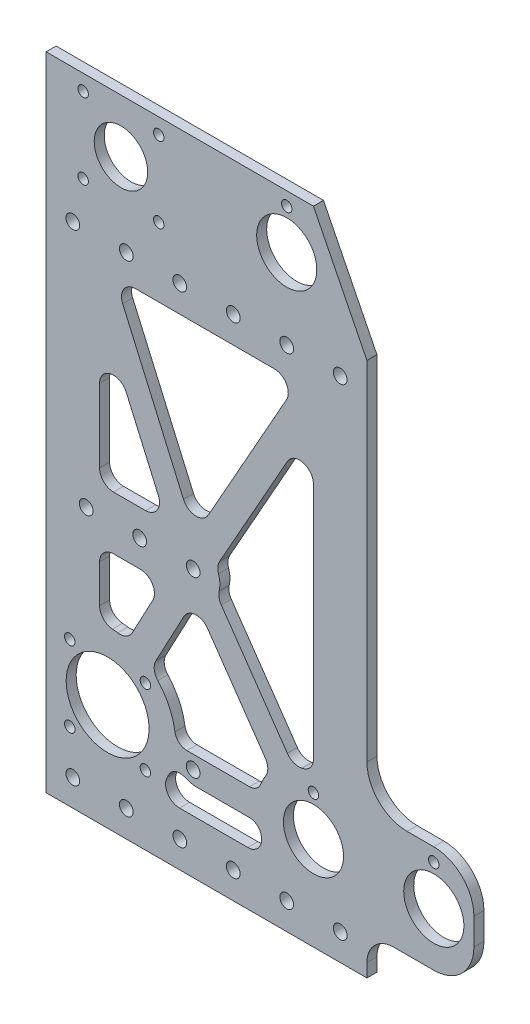
SolidWorks part; units mm, degrees
material "6061 Alloy"
ref_plane "Front Plane" through (0, 0, 0) normal (0, 0, 1) x (1, 0, 0)
ref_plane "Top Plane" through (0, 0, 0) normal (0, 1, 0) x (1, 0, 0)
ref_plane "Right Plane" through (0, 0, 0) normal (1, 0, 0) x (0, 0, -1)
sketch "Sketch1" plane through (0, 0, 0) normal (0, 0, 1) x (1, 0, 0)
  line L0 (0, 0) -> (76.2, 0) construction
  line L1 (76.2, 0) -> (76.2, 25.4)
  line L2 (76.2, 25.4) -> (50.8, 76.2)
  line L3 (50.8, 76.2) -> (12.7, 76.2)
  line L6 (-63.5, 12.7) -> (-38.1, 12.7) construction
  line L7 (76.2, 0) -> (76.2, -139.7)
  line L8 (0, 0) -> (-76.2, 0) construction
  line L9 (-76.2, 0) -> (-76.2, 76.2)
  line L10 (-76.2, 76.2) -> (12.7, 76.2)
  line L11 (76.2, -228.6) -> (0, -228.6)
  line L13 (63.5, -215.9) -> (38.1, -215.9) construction
  line L14 (-57.15, -101.6) -> (-31.75, -101.6) construction
  line L18 (95.25, -158.75) -> (107.95, -158.75)
  line L19 (127, -177.8) -> (127, -190.5)
  line L20 (107.95, -209.55) -> (88.9, -209.55)
  line L22 (76.2, -222.25) -> (76.2, -228.6)
  line L24 (-76.2, -177.8) -> (-46.99, -177.8) construction
  line L25 (-46.99, -177.8) -> (-29.0295, -195.7605) construction
  line L26 (-46.99, -177.8) -> (-29.0295, -195.7605) construction
  line L27 (-46.99, -177.8) -> (-64.9505, -195.7605) construction
  line L28 (-76.2, -228.6) -> (-76.2, 0)
  line L29 (0, -228.6) -> (-76.2, -228.6)
  circle A2 centre (-38.1, 12.7) radius 3.2639
  circle A3 centre (-12.7, 12.7) radius 3.2639
  circle A6 centre (-63.5, 12.7) radius 3.2639
  circle A7 centre (12.7, 12.7) radius 3.2639
  circle A8 centre (38.1, 12.7) radius 3.2639
  circle A9 centre (38.1, 50.8) radius 14.2875
  circle A12 centre (-22.6795, 32.8395) radius 2.4892
  circle A13 centre (-58.6005, 32.8395) radius 2.4892
  circle A14 centre (-58.6005, 68.7605) radius 2.4892
  circle A15 centre (-22.6795, 68.7605) radius 2.4892
  circle A16 centre (63.5, 12.7) radius 3.2639
  circle A17 centre (-40.64, 50.8) radius 12.7
  circle A18 centre (50.8, -184.15) radius 14.2875
  circle A19 centre (63.5, -215.9) radius 3.2639
  circle A20 centre (38.1, -215.9) radius 3.2639
  circle A21 centre (12.7, -215.9) radius 3.2639
  circle A22 centre (50.8, -165.1) radius 2.4892
  circle A23 centre (38.1, 69.85) radius 2.4892
  circle A26 centre (-6.35, -184.15) radius 3.2639
  circle A27 centre (107.95, -184.15) radius 14.2875
  circle A28 centre (107.95, -165.1) radius 2.4892
  circle A29 centre (-57.15, -101.6) radius 3.2639
  circle A30 centre (-31.75, -101.6) radius 3.2639
  circle A31 centre (-6.35, -101.6) radius 3.2639
  arc A32 (127, -190.5) -> (107.95, -209.55) centre (107.95, -190.5) cw
  arc A33 (76.2, -139.7) -> (95.25, -158.75) centre (95.25, -139.7) ccw
  arc A34 (127, -177.8) -> (107.95, -158.75) centre (107.95, -177.8) ccw
  arc A35 (76.2, -222.25) -> (88.9, -209.55) centre (88.9, -222.25) cw
  circle A36 centre (-46.99, -177.8) radius 19.685
  circle A37 centre (-46.99, -177.8) radius 25.4 construction
  circle A38 centre (-29.0295, -195.7605) radius 2.4892
  circle A42 centre (-64.9505, -195.7605) radius 2.4892
  circle A43 centre (-64.9505, -159.8395) radius 2.4892
  circle A44 centre (-29.0295, -159.8395) radius 2.4892
  circle A45 centre (-12.7, -215.9) radius 3.2639
  circle A46 centre (-38.1, -215.9) radius 3.2639
  circle A47 centre (-63.5, -215.9) radius 3.2639
  point P40 (-40.64, 50.8)
  point P71 (127, -209.55)
  point P74 (76.2, -158.75)
  point P77 (127, -158.75)
  point P80 (76.2, -209.55)
  dimension "D7" = 12.7
  dimension "D14" = 6.5278
  dimension "D16" = 28.575
  dimension "D18" = 50.8
  dimension "D20" = 12.7
  dimension "D21" = 4.9784
  dimension "D10" = 25.4
  dimension "D13" = 228.6
  dimension "D28" = 4.9784
  dimension "D29" = 4.9784
  dimension "D34" = 19.05
  dimension "D35" = 19.05
  dimension "D39" = 6.5278
  dimension "D41" = 6.5278
  dimension "D46" = 19.05
  dimension "D47" = 12.7
  dimension "D48" = 39.37
  dimension "D49" = 50.8
  dimension "D52" = 45
  dimension "D55" = 4.9784
  dimension "D1" = 76.2
  dimension "D2" = 76.2
  dimension "D3" = 88.9
  dimension "D4" = 38.1
  dimension "D5" = 25.4
  dimension "D6" = 38.1
  dimension "D8" = 6
  dimension "D11" = 25.4
  dimension "D12" = 184.15
  dimension "D15" = 35.56
  dimension "D17" = 50.8
  dimension "D19" = 25.4
  dimension "D23" = 12.7
  dimension "D9" = 25.4
  dimension "D25" = 25.4
  dimension "D26" = 76.2
  dimension "D27" = 19.05
  dimension "D30" = 19.05
  dimension "D31" = 50.8
  dimension "D32" = 19.05
  dimension "D33" = 76.2
  dimension "D36" = 25.4
  dimension "D37" = 50.8
  dimension "D38" = 6.35
  dimension "D40" = 76.2
  dimension "D42" = 127
  dimension "D43" = 57.15
  dimension "D45" = 25.4
  dimension "D53" = 46.99
  dimension "D54" = 50.8
  dimension "D58" = 90
  dimension "D24" = 6
  dimension "D44" = 3
  dimension "D22" = 4
  dimension "D57" = 4
extrude "Boss-Extrude1" add sketch "Sketch1" along normal blind 4.7625
sketch "Sketch2" plane through (0, 0, 4.7625) normal (0, 0, 1) x (1, 0, 0)
  line L3 (19.5993, -203.2) -> (-12.8308, -203.2)
  line L6 (-76.2, 76.2) -> (-76.2, -228.6) construction
  line L7 (50.8, 0) -> (-6.35, -101.6) construction
  line L8 (50.8, -157.1625) -> (50.8, -203.2) construction
  line L9 (-76.2, -228.6) -> (76.2, -228.6) construction
  line L10 (-46.99, -177.8) -> (-6.35, -101.6) construction
  line L11 (32.2225, 0) -> (-33.7713, 0)
  line L12 (50.8, 76.2) -> (-76.2, 76.2) construction
  line L13 (76.2, -228.6) -> (-76.2, -228.6)
  line L14 (-76.2, -228.6) -> (-76.2, 25.4)
  line L15 (-76.2, 25.4) -> (76.2, 25.4)
  line L16 (76.2, 25.4) -> (76.2, -228.6)
  line L17 (-6.35, -101.6) -> (-57.15, -101.6) construction
  line L20 (50.8, -184.15) -> (-6.35, -101.6) construction
  line L21 (7.0176, -109.7529) -> (38.3792, -155.0531)
  line L22 (27.9374, -162.2821) -> (0.5166, -122.6742)
  line L23 (-35.2875, -142.364) -> (-25.4996, -124.0118)
  line L24 (-10.7403, -123.3255) -> (-24.0816, -148.3405)
  line L25 (6.2012, -92.239) -> (38.4401, -34.9254)
  line L26 (-31.3267, -114.3) -> (-44.196, -114.3)
  line L27 (-6.35, -101.6) -> (-50.8, 0) construction
  line L28 (-39.8216, -9.251) -> (-10.9493, -75.2448)
  line L29 (-22.8847, -79.649) -> (-38.1457, -44.7667)
  line L30 (50.8, -12.9523) -> (50.8, 0) construction
  line L31 (50.8, 0) -> (43.5143, 0) construction
  line L32 (-50.8, -138.9112) -> (-50.8, -120.904)
  line L33 (-50.8, -145.6399) -> (-50.8, -203.2) construction
  line L34 (-50.8, -203.2) -> (-26.8995, -203.2) construction
  line L35 (-43.8689, 0) -> (-50.8, 0) construction
  line L36 (-50.8, -15.8426) -> (-50.8, 0) construction
  line L37 (50.8, -151.2141) -> (50.8, -38.1631)
  line L38 (50.8, -203.2) -> (31.684, -203.2) construction
  line L39 (-28.935, -88.9) -> (-44.196, -88.9)
  line L40 (0.8569, -75.8355) -> (37.9784, -9.8417)
  line L41 (-50.8, -82.296) -> (-50.8, -47.4137)
  line L42 (-6.35, -184.15) -> (-46.99, -177.8) construction
  line L43 (-6.35, -184.15) -> (50.8, -184.15) construction
  line L44 (20.4045, -190.5) -> (-5.4778, -190.5)
  line L45 (20.4045, -177.8) -> (-6.35, -177.8)
  line L46 (-7.1825, -190.2399) -> (-11.0358, -189.0357)
  line L47 (-6.35, -177.8) -> (-9.3211, -177.8)
  line L48 (-16.0792, -187.4596) -> (-46.99, -177.8) construction
  line L49 (-46.99, -177.8) -> (-14.605, -177.8) construction
  circle A2 centre (-46.99, -177.8) radius 19.685 construction
  arc A4 (-18.6167, -193.4123) -> (-17.8778, -191.987) centre (-46.99, -177.8) ccw
  circle A5 centre (50.8, -184.15) radius 14.2875 construction
  arc A7 (45.4943, -157.6892) -> (45.1834, -157.7534) centre (50.8, -184.15) ccw
  circle A8 centre (-6.35, -184.15) radius 3.2639 construction
  circle A9 centre (-6.35, -184.15) radius 3.2639 construction
  arc A10 (28.0698, -169.6013) -> (25.7163, -174.1934) centre (50.8, -184.15) ccw
  arc A11 (6.0167, -104.4907) -> (5.6941, -97.5715) centre (-6.35, -101.6) ccw
  arc A12 (-42.1097, -145.7848) -> (-44.6693, -145.4983) centre (-46.99, -177.8) ccw
  arc A13 (27.9374, -162.2821) -> (28.0698, -169.6013) centre (22.5076, -166.0411) cw
  arc A14 (25.7332, -194.1491) -> (19.5993, -203.2) centre (19.5993, -196.596) cw
  arc A15 (-18.6167, -193.4123) -> (-12.8308, -203.2) centre (-12.8308, -196.596) ccw
  arc A16 (-24.0816, -148.3405) -> (-23.1218, -155.9117) centre (-18.2545, -151.4482) ccw
  arc A17 (-35.2875, -142.364) -> (-42.1097, -145.7848) centre (-41.1145, -139.2562) cw
  arc A18 (-44.6693, -145.4983) -> (-50.8, -138.9112) centre (-44.196, -138.9112) cw
  arc A19 (-50.8, -120.904) -> (-44.196, -114.3) centre (-44.196, -120.904) cw
  arc A20 (-25.4996, -124.0118) -> (-31.3267, -114.3) centre (-31.3267, -120.904) ccw
  arc A21 (45.4943, -157.6892) -> (50.8, -151.2141) centre (44.196, -151.2141) ccw
  arc A22 (38.3792, -155.0531) -> (45.1834, -157.7534) centre (43.809, -151.294) ccw
  arc A23 (7.0176, -109.7529) -> (6.0167, -104.4907) centre (12.4473, -105.9938) cw
  arc A24 (6.2012, -92.239) -> (5.6941, -97.5715) centre (11.9571, -95.4767) ccw
  arc A25 (38.4401, -34.9254) -> (50.8, -38.1631) centre (44.196, -38.1631) cw
  arc A26 (37.9784, -9.8417) -> (32.2225, 0) centre (32.2225, -6.604) ccw
  arc A27 (-39.8216, -9.251) -> (-33.7713, 0) centre (-33.7713, -6.604) cw
  arc A28 (0.8569, -75.8355) -> (-10.9493, -75.2448) centre (-4.899, -72.5978) cw
  arc A29 (-22.8847, -79.649) -> (-28.935, -88.9) centre (-28.935, -82.296) cw
  arc A30 (-44.196, -88.9) -> (-50.8, -82.296) centre (-44.196, -82.296) cw
  arc A31 (-50.8, -47.4137) -> (-38.1457, -44.7667) centre (-44.196, -47.4137) cw
  arc A32 (-10.7403, -123.3255) -> (0.5166, -122.6742) centre (-4.9132, -126.4332) cw
  arc A33 (25.7163, -194.1066) -> (25.7332, -194.1491) centre (50.8, -184.15) ccw
  arc A34 (-14.9714, -172.9423) -> (-23.1218, -155.9117) centre (-46.99, -177.8) ccw
  arc A35 (20.4045, -177.8) -> (25.7163, -174.1934) centre (20.4045, -172.085) ccw
  arc A36 (-9.3211, -177.8) -> (-14.9714, -172.9423) centre (-9.3211, -172.085) cw
  arc A37 (25.7163, -194.1066) -> (20.4045, -190.5) centre (20.4045, -196.215) ccw
  arc A38 (-5.4778, -190.5) -> (-7.1825, -190.2399) centre (-5.4778, -184.785) cw
  arc A39 (-17.8778, -191.987) -> (-11.0358, -189.0357) centre (-12.7404, -194.4906) cw
  point P22 (-31.75, -101.6)
  point P67 (30.6488, -166.1985)
  point P78 (-37.6488, -146.7915)
  point P93 (5.1314, -107.0284)
  point P111 (-50.8, -88.9)
  point P115 (24.5702, -190.5)
  point P120 (-6.35, -190.5)
  circle M16 centre (-6.35, -184.15) radius 3.2639
  dimension "D6" = 12.7
  dimension "D7" = 25.4
  dimension "D8" = 25.4
  dimension "D17" = 12.7
  dimension "D3" = 12.7
  dimension "D18" = 12.7
  dimension "D19" = 6.604
  dimension "D20" = 6.604
  dimension "D23" = 5.715
  dimension "D2" = 76.2
  dimension "D4" = 25.4
  dimension "D5" = 50.8
  dimension "D9" = 12.7
  dimension "D10" = 6.35
  dimension "D11" = 6.35
  dimension "D12" = 12.7
  dimension "D13" = 6.35
  dimension "D14" = 12.7
  dimension "D15" = 6.35
  dimension "D16" = 12.7
  dimension "D21" = 6.35
  dimension "D22" = 12.7
extrude "Cut-Extrude1" cut sketch "Sketch2" against normal through all contours A25 L25 A24 A11 A23 L21 A22 A7 A21 L37 | A28 L40 A26 L11 A27 L28 | A31 L41 A30 L39 A29 L29 | A32 L24 A16 A4 A15 L3 A14 A10 A13 L22 M16 | L23 A20 L26 A19 L32 A18 A12 A17
